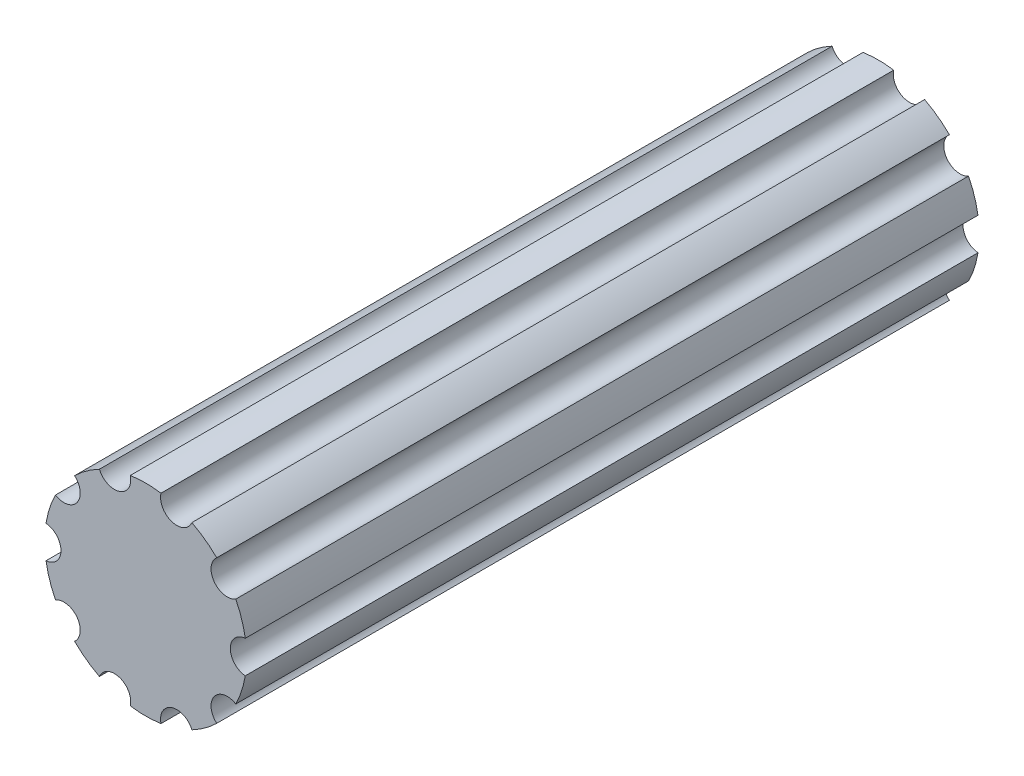
SolidWorks part; units mm, degrees
ref_plane "Front" through (0, 0, 0) normal (0, 0, 1) x (1, 0, 0)
ref_plane "Top" through (0, 0, 0) normal (0, 1, 0) x (1, 0, 0)
ref_plane "Right" through (0, 0, 0) normal (1, 0, 0) x (0, 0, -1)
sketch "Sketch1" plane through (0, 0, 0) normal (0, 0, 1) x (1, 0, 0)
  line L0 (0, 0) -> (0.7874, 0) construction
  line L1 (0, 0) -> (0, 0.7874) construction
  arc A0 (-0.3605, 0.7) -> (-0.5543, 0.5592) centre (0, 0) ccw
  arc A1 (0.7772, -0.1266) -> (0.7772, 0.1266) centre (0.7874, 0) cw
  arc A2 (0.5543, -0.5592) -> (0.7031, -0.3544) centre (0.637, -0.4628) cw
  arc A3 (0.1198, -0.7782) -> (0.3605, -0.7) centre (0.2433, -0.7489) cw
  arc A4 (-0.3605, -0.7) -> (-0.1198, -0.7782) centre (-0.2433, -0.7489) cw
  arc A5 (-0.7031, -0.3544) -> (-0.5543, -0.5592) centre (-0.637, -0.4628) cw
  arc A6 (-0.7772, 0.1266) -> (-0.7772, -0.1266) centre (-0.7874, 0) cw
  arc A7 (-0.5543, 0.5592) -> (-0.7031, 0.3544) centre (-0.637, 0.4628) cw
  arc A8 (-0.1198, 0.7782) -> (-0.3605, 0.7) centre (-0.2433, 0.7489) cw
  arc A9 (0.3605, 0.7) -> (0.1198, 0.7782) centre (0.2433, 0.7489) cw
  arc A10 (0.7031, 0.3544) -> (0.5543, 0.5592) centre (0.637, 0.4628) cw
  arc A11 (-0.7031, 0.3544) -> (-0.7772, 0.1266) centre (0, 0) ccw
  arc A12 (-0.7772, -0.1266) -> (-0.7031, -0.3544) centre (0, 0) ccw
  arc A13 (-0.5543, -0.5592) -> (-0.3605, -0.7) centre (0, 0) ccw
  arc A14 (-0.1198, -0.7782) -> (0.1198, -0.7782) centre (0, 0) ccw
  arc A15 (0.3605, -0.7) -> (0.5543, -0.5592) centre (0, 0) ccw
  arc A16 (0.7031, -0.3544) -> (0.7772, -0.1266) centre (0, 0) ccw
  arc A17 (0.7772, 0.1266) -> (0.7031, 0.3544) centre (0, 0) ccw
  arc A18 (0.5543, 0.5592) -> (0.3605, 0.7) centre (0, 0) ccw
  arc A19 (0.1198, 0.7782) -> (-0.1198, 0.7782) centre (0, 0) ccw
  point P36 (0, 0)
  dimension "D1" = 10
extrude "Boss-Extrude1" add sketch "Sketch1" along normal blind 5.715
